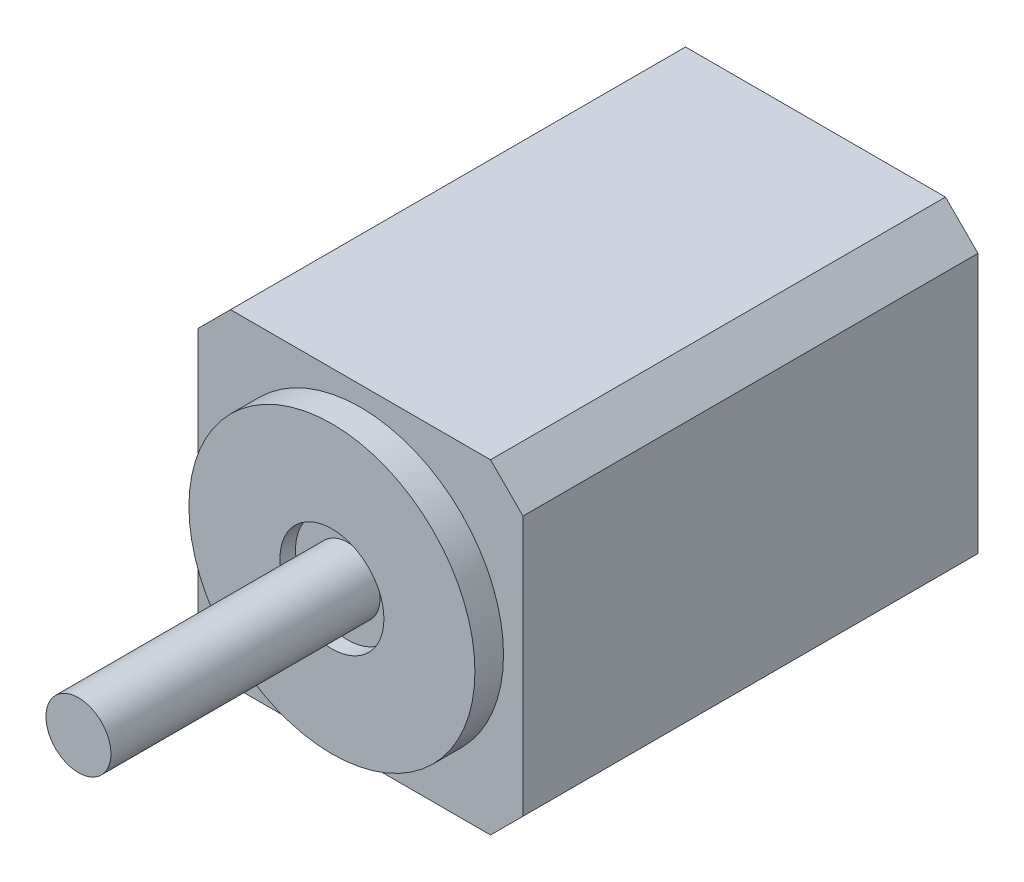
SolidWorks part; units mm, degrees
material "Plain Carbon Steel"
ref_plane "Front Plane" through (0, 0, 0) normal (0, 0, 1) x (1, 0, 0)
ref_plane "Top Plane" through (0, 0, 0) normal (0, 1, 0) x (1, 0, 0)
ref_plane "Right Plane" through (0, 0, 0) normal (1, 0, 0) x (0, 0, -1)
sketch "Sketch1" plane through (0, 0, 0) normal (0, 0, 1) x (1, 0, 0)
  line L1 (-12.5, -12.5) -> (12.5, -12.5)
  line L2 (-12.5, -12.5) -> (-12.5, 12.5)
  line L3 (-12.5, 12.5) -> (12.5, 12.5)
  line L4 (12.5, -12.5) -> (12.5, 12.5)
  line L5 (-12.5, -12.5) -> (12.5, 12.5) construction
  line L6 (-12.5, 12.5) -> (12.5, -12.5) construction
  point P1 (0, 0)
  dimension "D1" = 25
  dimension "D2" = 25
extrude "Boss-Extrude1" add sketch "Sketch1" along normal blind 35
sketch "Sketch2" plane through (0, 0, 35) normal (0, 0, 1) x (1, 0, 0)
  circle A0 centre (0, 0) radius 11
  dimension "D1" = 22
extrude "Boss-Extrude2" add sketch "Sketch2" along normal blind 2.2
chamfer "Chamfer1" distance 2.5 angle 45 4 edges at (-12.5, -12.5, 17.5) (12.5, -12.5, 17.5) (12.5, 12.5, 17.5) (-12.5, 12.5, 17.5)
sketch "Sketch4" plane through (0, 0, 37.2) normal (0, 0, 1) x (1, 0, 0)
  circle A0 centre (0, 0) radius 4
  dimension "D1" = 8
extrude "Cut-Extrude1" cut sketch "Sketch4" against normal blind 1.2
sketch "Sketch3" plane through (0, 0, 36) normal (0, 0, 1) x (1, 0, 0)
  circle A0 centre (0, 0) radius 2.5
  dimension "D1" = 5
extrude "Boss-Extrude3" add sketch "Sketch3" along normal blind 20.7
